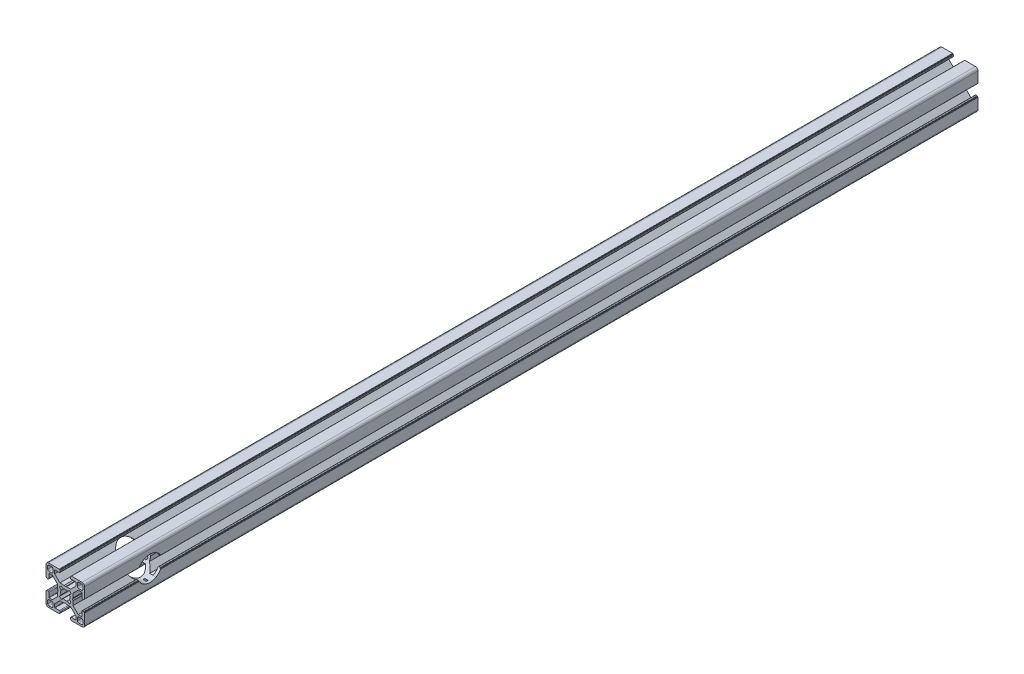
SolidWorks part; units mm, degrees
material "6061 Alloy"
ref_plane "Front" through (0, 0, 0) normal (0, 0, 1) x (1, 0, 0)
ref_plane "Top" through (0, 0, 0) normal (0, 1, 0) x (1, 0, 0)
ref_plane "Right" through (0, 0, 0) normal (1, 0, 0) x (0, 0, -1)
sketch "Sketch1" plane through (0, 0, 0) normal (0, 0, 1) x (1, 0, 0)
  line L0 (13.7, 12.7) -> (13.7, 10.5)
  line L1 (10.5, 9.5) -> (12.7, 9.5)
  line L2 (9.5, 12.7) -> (9.5, 10.5)
  line L3 (10.5, 13.7) -> (12.7, 13.7)
  line L4 (3.1359, 4.5184) -> (1.6001, 3.2806)
  line L5 (3.2806, 1.6001) -> (4.5053, 3.1547)
  line L6 (6.0045, 0.9) -> (5.4849, 0)
  line L7 (6.0045, 4.2045) -> (6.0045, 0.9)
  line L8 (0, -5.4849) -> (0.9, -6)
  line L9 (0.9, -6) -> (4.2045, -6)
  line L10 (4.2045, -6) -> (8.25, -10.05)
  line L11 (8.25, -10.05) -> (8.25, -12.6)
  line L12 (4.65, -12.8) -> (8.05, -12.8)
  line L13 (4.05, -14.3) -> (4.05, -13.4)
  line L14 (4.25, -14.5) -> (4.35, -14.5)
  line L15 (4.55, -14.8) -> (4.55, -14.7)
  line L16 (4.75, -15) -> (13, -15)
  line L17 (15, -13) -> (15, -4.75)
  line L18 (14.7, -4.55) -> (14.8, -4.55)
  line L19 (14.5, -4.35) -> (14.5, -4.25)
  line L20 (13.4, -4.05) -> (14.3, -4.05)
  line L21 (12.8, -8.05) -> (12.8, -4.65)
  line L22 (12.6, -8.25) -> (10.05, -8.25)
  line L23 (10.05, -8.25) -> (6.0045, -4.2045)
  line L24 (6.0045, -4.2045) -> (6.0045, -0.9)
  line L25 (6.0045, -0.9) -> (5.4849, 0)
  line L26 (10.05, 8.25) -> (6.0045, 4.2045)
  line L27 (12.6, 8.25) -> (10.05, 8.25)
  line L28 (12.8, 8.05) -> (12.8, 4.65)
  line L29 (13.4, 4.05) -> (14.3, 4.05)
  line L30 (14.5, 4.35) -> (14.5, 4.25)
  line L31 (14.7, 4.55) -> (14.8, 4.55)
  line L32 (15, 13) -> (15, 4.75)
  line L33 (4.75, 15) -> (13, 15)
  line L34 (4.55, 14.8) -> (4.55, 14.7)
  line L35 (4.25, 14.5) -> (4.35, 14.5)
  line L36 (4.05, 14.3) -> (4.05, 13.4)
  line L37 (4.65, 12.8) -> (8.05, 12.8)
  line L38 (8.25, 10.05) -> (8.25, 12.6)
  line L39 (4.2045, 6) -> (8.25, 10.05)
  line L40 (0.9, 6) -> (4.2045, 6)
  line L41 (0, 5.4849) -> (0.9, 6)
  line L42 (-13.7, -12.7) -> (-13.7, -10.5)
  line L43 (-10.5, -9.5) -> (-12.7, -9.5)
  line L44 (-9.5, -12.7) -> (-9.5, -10.5)
  line L45 (-10.5, -13.7) -> (-12.7, -13.7)
  line L46 (-3.1359, -4.5184) -> (-1.6001, -3.2806)
  line L47 (-3.2806, -1.6001) -> (-4.5053, -3.1547)
  line L48 (0, 5.4849) -> (-0.9, 6)
  line L49 (-0.9, 6) -> (-4.2045, 6)
  line L50 (-4.2045, 6) -> (-8.25, 10.05)
  line L51 (-8.25, 10.05) -> (-8.25, 12.6)
  line L52 (-4.65, 12.8) -> (-8.05, 12.8)
  line L53 (-4.05, 14.3) -> (-4.05, 13.4)
  line L54 (-4.25, 14.5) -> (-4.35, 14.5)
  line L55 (-4.55, 14.8) -> (-4.55, 14.7)
  line L56 (-4.75, 15) -> (-13, 15)
  line L57 (-15, 13) -> (-15, 4.75)
  line L58 (-14.7, 4.55) -> (-14.8, 4.55)
  line L59 (-14.5, 4.35) -> (-14.5, 4.25)
  line L60 (-13.4, 4.05) -> (-14.3, 4.05)
  line L61 (-12.8, 8.05) -> (-12.8, 4.65)
  line L62 (-12.6, 8.25) -> (-10.05, 8.25)
  line L63 (-10.05, 8.25) -> (-6.0045, 4.2045)
  line L64 (-6.0045, -0.9) -> (-5.4849, 0)
  line L65 (-6.0045, -4.2045) -> (-6.0045, -0.9)
  line L66 (-10.05, -8.25) -> (-6.0045, -4.2045)
  line L67 (-12.6, -8.25) -> (-10.05, -8.25)
  line L68 (-12.8, -8.05) -> (-12.8, -4.65)
  line L69 (-13.4, -4.05) -> (-14.3, -4.05)
  line L70 (-14.5, -4.35) -> (-14.5, -4.25)
  line L71 (-14.7, -4.55) -> (-14.8, -4.55)
  line L72 (-15, -13) -> (-15, -4.75)
  line L73 (-4.75, -15) -> (-13, -15)
  line L74 (-4.55, -14.8) -> (-4.55, -14.7)
  line L75 (-4.25, -14.5) -> (-4.35, -14.5)
  line L76 (-4.05, -14.3) -> (-4.05, -13.4)
  line L77 (3.2806, -1.6001) -> (4.5053, -3.1547)
  line L78 (3.1359, -4.5184) -> (1.6001, -3.2806)
  line L79 (-4.65, -12.8) -> (-8.05, -12.8)
  line L80 (-8.25, -10.05) -> (-8.25, -12.6)
  line L81 (-4.2045, -6) -> (-8.25, -10.05)
  line L82 (-0.9, -6) -> (-4.2045, -6)
  line L83 (0, -5.4849) -> (-0.9, -6)
  line L84 (10.5, -13.7) -> (12.7, -13.7)
  line L85 (9.5, -12.7) -> (9.5, -10.5)
  line L86 (10.5, -9.5) -> (12.7, -9.5)
  line L87 (13.7, -12.7) -> (13.7, -10.5)
  line L88 (-6.0045, 4.2045) -> (-6.0045, 0.9)
  line L89 (-6.0045, 0.9) -> (-5.4849, 0)
  line L90 (-3.2806, 1.6001) -> (-4.5053, 3.1547)
  line L91 (-3.1359, 4.5184) -> (-1.6001, 3.2806)
  line L92 (-10.5, 13.7) -> (-12.7, 13.7)
  line L93 (-9.5, 12.7) -> (-9.5, 10.5)
  line L94 (-10.5, 9.5) -> (-12.7, 9.5)
  line L95 (-13.7, 12.7) -> (-13.7, 10.5)
  line L96 (-23.4857, 0) -> (20.9308, 0) construction
  line L97 (0, 17.9563) -> (0, -17.361) construction
  arc A0 (13.7, 12.7) -> (12.7, 13.7) centre (12.7, 12.7) ccw
  arc A1 (12.7, 9.5) -> (13.7, 10.5) centre (12.7, 10.5) ccw
  arc A2 (9.5, 10.5) -> (10.5, 9.5) centre (10.5, 10.5) ccw
  arc A3 (10.5, 13.7) -> (9.5, 12.7) centre (10.5, 12.7) ccw
  arc A4 (1.6001, 3.2806) -> (-1.6001, 3.2806) centre (0, 0) ccw
  arc A5 (8.25, -12.6) -> (8.05, -12.8) centre (8.05, -12.6) cw
  arc A6 (4.65, -12.8) -> (4.05, -13.4) centre (4.65, -13.4) ccw
  arc A7 (4.05, -14.3) -> (4.25, -14.5) centre (4.25, -14.3) ccw
  arc A8 (4.35, -14.5) -> (4.55, -14.7) centre (4.35, -14.7) cw
  arc A9 (4.55, -14.8) -> (4.75, -15) centre (4.75, -14.8) ccw
  arc A10 (13, -15) -> (15, -13) centre (13, -13) ccw
  arc A11 (15, -4.75) -> (14.8, -4.55) centre (14.8, -4.75) ccw
  arc A12 (14.7, -4.55) -> (14.5, -4.35) centre (14.7, -4.35) cw
  arc A13 (14.5, -4.25) -> (14.3, -4.05) centre (14.3, -4.25) ccw
  arc A14 (13.4, -4.05) -> (12.8, -4.65) centre (13.4, -4.65) ccw
  arc A15 (12.8, -8.05) -> (12.6, -8.25) centre (12.6, -8.05) cw
  arc A16 (4.5053, 3.1547) -> (3.1359, 4.5184) centre (0, 0) ccw
  arc A17 (12.8, 8.05) -> (12.6, 8.25) centre (12.6, 8.05) ccw
  arc A18 (13.4, 4.05) -> (12.8, 4.65) centre (13.4, 4.65) cw
  arc A19 (14.5, 4.25) -> (14.3, 4.05) centre (14.3, 4.25) cw
  arc A20 (14.7, 4.55) -> (14.5, 4.35) centre (14.7, 4.35) ccw
  arc A21 (15, 4.75) -> (14.8, 4.55) centre (14.8, 4.75) cw
  arc A22 (13, 15) -> (15, 13) centre (13, 13) cw
  arc A23 (4.55, 14.8) -> (4.75, 15) centre (4.75, 14.8) cw
  arc A24 (4.35, 14.5) -> (4.55, 14.7) centre (4.35, 14.7) ccw
  arc A25 (4.05, 14.3) -> (4.25, 14.5) centre (4.25, 14.3) cw
  arc A26 (4.65, 12.8) -> (4.05, 13.4) centre (4.65, 13.4) cw
  arc A27 (8.25, 12.6) -> (8.05, 12.8) centre (8.05, 12.6) ccw
  arc A28 (-13.7, -12.7) -> (-12.7, -13.7) centre (-12.7, -12.7) ccw
  arc A29 (-12.7, -9.5) -> (-13.7, -10.5) centre (-12.7, -10.5) ccw
  arc A30 (-9.5, -10.5) -> (-10.5, -9.5) centre (-10.5, -10.5) ccw
  arc A31 (-10.5, -13.7) -> (-9.5, -12.7) centre (-10.5, -12.7) ccw
  arc A32 (-4.5053, -3.1547) -> (-3.1359, -4.5184) centre (0, 0) ccw
  arc A33 (-3.2806, 1.6001) -> (-3.2806, -1.6001) centre (0, 0) ccw
  arc A34 (-8.25, 12.6) -> (-8.05, 12.8) centre (-8.05, 12.6) cw
  arc A35 (-4.65, 12.8) -> (-4.05, 13.4) centre (-4.65, 13.4) ccw
  arc A36 (-4.05, 14.3) -> (-4.25, 14.5) centre (-4.25, 14.3) ccw
  arc A37 (-4.35, 14.5) -> (-4.55, 14.7) centre (-4.35, 14.7) cw
  arc A38 (-4.55, 14.8) -> (-4.75, 15) centre (-4.75, 14.8) ccw
  arc A39 (-13, 15) -> (-15, 13) centre (-13, 13) ccw
  arc A40 (-15, 4.75) -> (-14.8, 4.55) centre (-14.8, 4.75) ccw
  arc A41 (-14.7, 4.55) -> (-14.5, 4.35) centre (-14.7, 4.35) cw
  arc A42 (-14.5, 4.25) -> (-14.3, 4.05) centre (-14.3, 4.25) ccw
  arc A43 (-13.4, 4.05) -> (-12.8, 4.65) centre (-13.4, 4.65) ccw
  arc A44 (-12.8, 8.05) -> (-12.6, 8.25) centre (-12.6, 8.05) cw
  arc A45 (-4.5053, 3.1547) -> (-3.1359, 4.5184) centre (0, 0) cw
  arc A46 (-12.8, -8.05) -> (-12.6, -8.25) centre (-12.6, -8.05) ccw
  arc A47 (-13.4, -4.05) -> (-12.8, -4.65) centre (-13.4, -4.65) cw
  arc A48 (-14.5, -4.25) -> (-14.3, -4.05) centre (-14.3, -4.25) cw
  arc A49 (3.2806, 1.6001) -> (3.2806, -1.6001) centre (0, 0) cw
  arc A50 (4.5053, -3.1547) -> (3.1359, -4.5184) centre (0, 0) cw
  arc A51 (1.6001, -3.2806) -> (-1.6001, -3.2806) centre (0, 0) cw
  arc A52 (-14.7, -4.55) -> (-14.5, -4.35) centre (-14.7, -4.35) ccw
  arc A53 (-15, -4.75) -> (-14.8, -4.55) centre (-14.8, -4.75) cw
  arc A54 (-13, -15) -> (-15, -13) centre (-13, -13) cw
  arc A55 (-4.55, -14.8) -> (-4.75, -15) centre (-4.75, -14.8) cw
  arc A56 (10.5, -13.7) -> (9.5, -12.7) centre (10.5, -12.7) cw
  arc A57 (9.5, -10.5) -> (10.5, -9.5) centre (10.5, -10.5) cw
  arc A58 (12.7, -9.5) -> (13.7, -10.5) centre (12.7, -10.5) cw
  arc A59 (13.7, -12.7) -> (12.7, -13.7) centre (12.7, -12.7) cw
  arc A60 (-4.35, -14.5) -> (-4.55, -14.7) centre (-4.35, -14.7) ccw
  arc A61 (-4.05, -14.3) -> (-4.25, -14.5) centre (-4.25, -14.3) cw
  arc A62 (-4.65, -12.8) -> (-4.05, -13.4) centre (-4.65, -13.4) cw
  arc A63 (-8.25, -12.6) -> (-8.05, -12.8) centre (-8.05, -12.6) ccw
  arc A64 (-10.5, 13.7) -> (-9.5, 12.7) centre (-10.5, 12.7) cw
  arc A65 (-9.5, 10.5) -> (-10.5, 9.5) centre (-10.5, 10.5) cw
  arc A66 (-12.7, 9.5) -> (-13.7, 10.5) centre (-12.7, 10.5) cw
  arc A67 (-13.7, 12.7) -> (-12.7, 13.7) centre (-12.7, 12.7) cw
  point P81 (15, 15)
  point P82 (0, 15)
  point P203 (0, -15)
  point P204 (15, -15)
  point P206 (0, 0)
  point P207 (15, 0)
  point P219 (-15, 0)
  point P220 (-15, -15)
  point P221 (-15, 15)
  dimension "D6" = 7.3
  dimension "D7" = 11
  dimension "D1" = 30
  dimension "D2" = 15
  dimension "D3" = 30
  dimension "D4" = 8.1
  dimension "D5" = 9
  dimension "D8" = 8.1
extrude "Boss-Extrude1" add sketch "Sketch1" along normal blind 694.69
sketch "Sketch3" plane through (-15, 0, 0) normal (-1, 0, 0) x (0, 0, 1)
  line L0 (694.69, -15) -> (0, -15) construction
  line L1 (694.69, 13) -> (694.69, 4.75) construction
  circle A0 centre (643.89, 0) radius 9.525
  dimension "D2" = 19.05
  dimension "D3" = 50.8
  dimension "D1" = 15
extrude "Cut-Extrude1" cut sketch "Sketch3" against normal up to next
